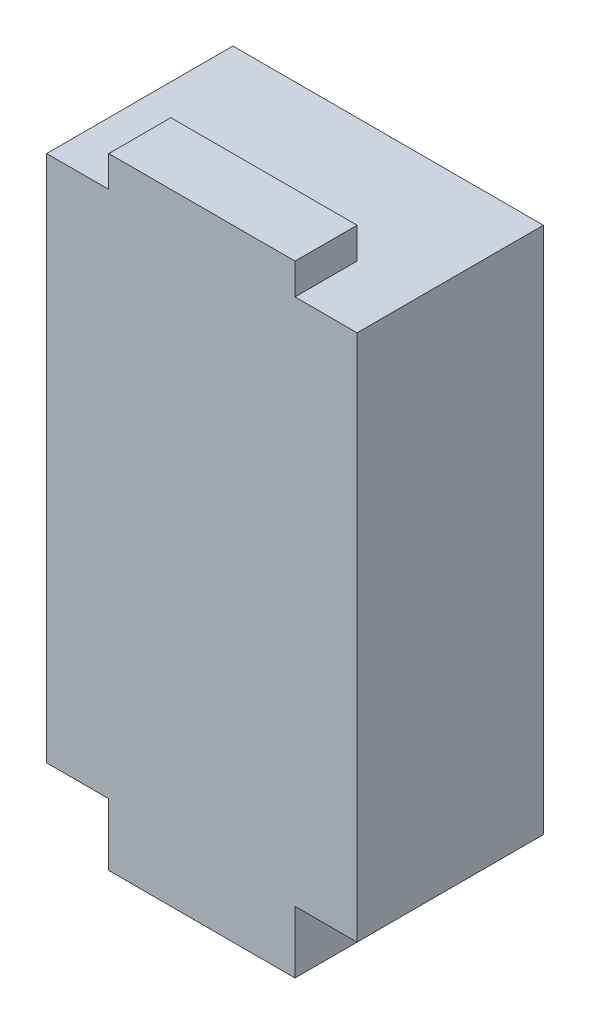
SolidWorks part; units mm, degrees
material "PVC Rigid"
ref_plane "Front Plane" through (0, 0, 0) normal (0, 0, 1) x (1, 0, 0)
ref_plane "Top Plane" through (0, 0, 0) normal (0, 1, 0) x (1, 0, 0)
ref_plane "Right Plane" through (0, 0, 0) normal (1, 0, 0) x (0, 0, -1)
sketch "Sketch1" plane through (0, 0, 0) normal (0, 0, 1) x (1, 0, 0)
  line L1 (-10, 0) -> (-40, 0)
  line L2 (0, 10) -> (0, 95)
  line L3 (-10, 100) -> (-40, 100)
  line L4 (-50, 10) -> (-50, 95)
  line L7 (-50, 10) -> (-40, 10)
  line L8 (-40, 0) -> (-40, 10)
  line L11 (0, 10) -> (-10, 10)
  line L12 (-10, 0) -> (-10, 10)
  line L15 (-50, 95) -> (-40, 95)
  line L16 (-40, 100) -> (-40, 95)
  line L19 (0, 95) -> (-10, 95)
  line L20 (-10, 100) -> (-10, 95)
  dimension "D3" = 10
  dimension "D4" = 5
  dimension "D5" = 10
  dimension "D6" = 5
  dimension "D7" = 10
  dimension "D8" = 10
  dimension "D9" = 10
  dimension "D10" = 10
extrude "Boss-Extrude1" add sketch "Sketch1" along normal blind 10
sketch "Sketch2" plane through (0, 0, 0) normal (0, 0, -1) x (-1, 0, 0)
  line L1 (50, 95) -> (0, 95)
  line L2 (50, 95) -> (50, 10)
  line L3 (50, 10) -> (0, 10)
  line L4 (0, 95) -> (0, 10)
extrude "Boss-Extrude2" add sketch "Sketch2" along normal blind 20
sketch "Sketch3" plane through (0, 0, -20) normal (0, 0, -1) x (-1, 0, 0)
  line L0 (0, 10) -> (50, 10) construction
  line L2 (50, 10) -> (50, 95) construction
  circle A0 centre (25, 35) radius 6
  dimension "D1" = 25
  dimension "D3" = 12
  dimension "D2" = 25
extrude "Cut-Extrude1" cut sketch "Sketch3" against normal blind 20
